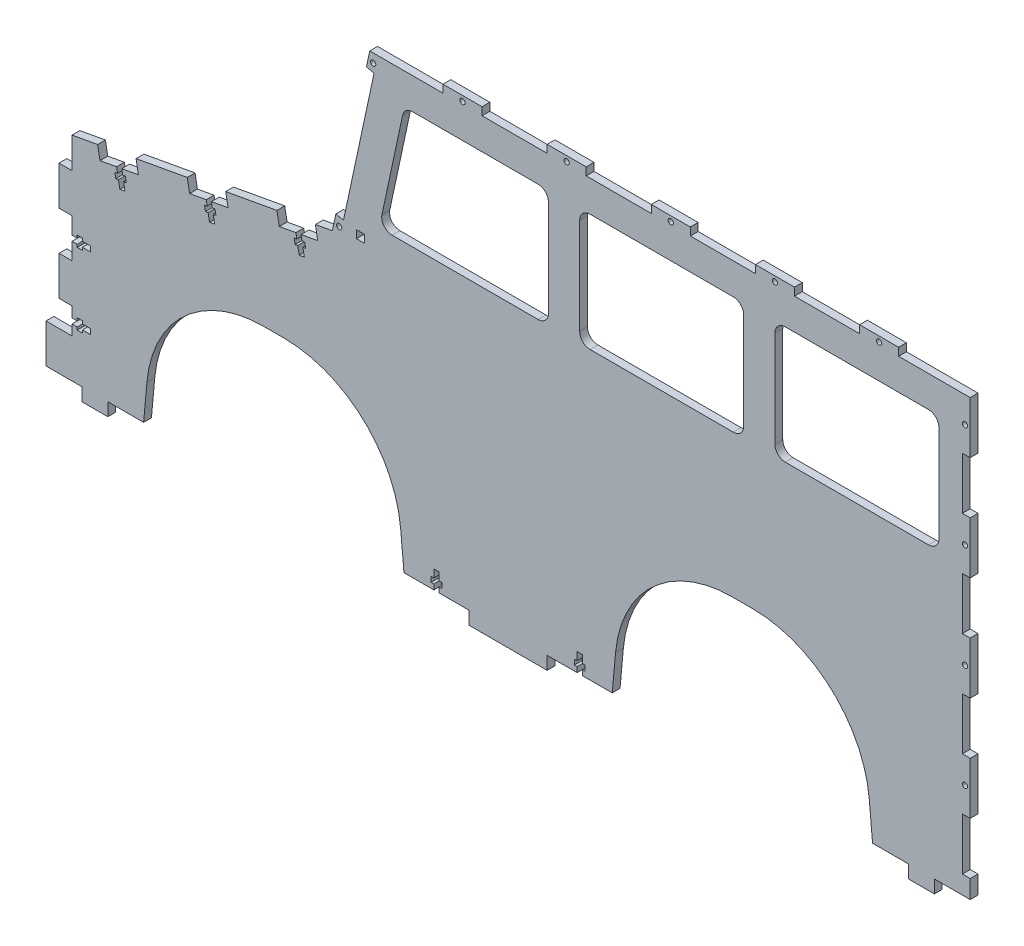
SolidWorks part; units mm, degrees
ref_plane "Front" through (0, 0, 0) normal (0, 0, 1) x (1, 0, 0)
ref_plane "Top" through (0, 0, 0) normal (0, 1, 0) x (1, 0, 0)
ref_plane "Right" through (0, 0, 0) normal (1, 0, 0) x (0, 0, -1)
sketch "草图1" plane through (0, 0, 0) normal (0, 0, 1) x (1, 0, 0)
  line L0 (0, 0) -> (0, 85)
  line L3 (125, 175) -> (355, 175)
  line L4 (355, 175) -> (355, 0)
  line L5 (355, 0) -> (317.5, 0)
  line L7 (312.5, 60) -> (222.5, 60)
  line L9 (217.5, 0) -> (137.5, 0)
  line L11 (132.5, 60) -> (42.5, 60)
  line L13 (37.5, 0) -> (0, 0)
  line L14 (37.5, 0) -> (37.5, 5)
  line L15 (37.5, 5) -> (42.5, 60)
  line L16 (137.5, 0) -> (137.5, 5)
  line L17 (137.5, 5) -> (132.5, 60)
  line L18 (217.5, 0) -> (217.5, 5)
  line L19 (217.5, 5) -> (222.5, 60)
  line L22 (312.5, 60) -> (317.5, 5)
  line L23 (317.5, 5) -> (317.5, 0)
  line L24 (125, 175) -> (110, 105)
  line L25 (110, 105) -> (0, 85)
  dimension "D1" = 85
  dimension "D2" = 37.5
  dimension "D3" = 0
  dimension "D4" = 100
  dimension "D5" = 90
  dimension "D6" = 80
  dimension "D7" = 100
  dimension "D8" = 90
  dimension "D9" = 37.5
  dimension "D10" = 70
  dimension "D11" = 20
  dimension "D12" = 5
  dimension "D13" = 15
  dimension "D15" = 60
  dimension "D16" = 60
  dimension "D18" = 230
  dimension "D19" = 5
  dimension "D20" = 5
  dimension "D21" = 5
extrude "凸台-拉伸1" add sketch "草图1" along normal blind 3
sketch "草图2" plane through (0, 0, 3) normal (0, 0, 1) x (1, 0, 0)
  line L0 (355, 175) -> (125, 175) construction
  circle A1 centre (200, 173) radius 1
  circle A2 centre (240, 173) radius 1
  circle A3 centre (280, 173) radius 1
  circle A4 centre (320, 173) radius 1
  circle A5 centre (160, 173) radius 1
  dimension "D2" = 2
  dimension "D3" = 40
  dimension "D4" = 2
  dimension "D7" = 0
  dimension "D8" = 40
  dimension "D9" = 40
  dimension "D10" = 2
  dimension "D11" = 40
  dimension "D12" = 0
sketch "草图3" plane through (0, 0, 3) normal (0, 0, 1) x (1, 0, 0)
  line L0 (355, 175) -> (125, 175) construction
  line L4 (167.5, 175) -> (167.5, 172)
  line L5 (355, 172) -> (327.5, 172)
  line L9 (207.5, 175) -> (207.5, 172)
  line L13 (247.5, 175) -> (247.5, 172)
  line L17 (287.5, 175) -> (287.5, 172)
  line L19 (312.5, 175) -> (312.5, 172)
  line L21 (327.5, 175) -> (327.5, 172)
  line L22 (355, 0) -> (355, 175) construction
  line L25 (192.5, 172) -> (167.5, 172)
  line L26 (232.5, 172) -> (207.5, 172)
  line L27 (272.5, 172) -> (247.5, 172)
  line L28 (312.5, 172) -> (287.5, 172)
  line L31 (167.5, 175) -> (192.5, 175)
  line L32 (207.5, 175) -> (232.5, 175)
  line L33 (247.5, 175) -> (272.5, 175)
  line L34 (287.5, 175) -> (312.5, 175)
  line L35 (327.5, 175) -> (355, 175)
  line L36 (355, 175) -> (355, 172)
  line L37 (152.5, 175) -> (152.5, 172)
  line L38 (192.5, 175) -> (192.5, 172)
  line L39 (232.5, 175) -> (232.5, 172)
  line L40 (272.5, 175) -> (272.5, 172)
  line L41 (152.5, 172) -> (124.3571, 172)
  line L42 (125, 175) -> (110, 105) construction
  line L44 (152.5, 175) -> (125, 175)
  line L45 (125, 175) -> (124.3571, 172)
  circle A4 centre (320, 173) radius 1 construction
  dimension "D15" = 7.5
  dimension "D1" = 15
  dimension "D2" = 3
  dimension "D4" = 3
  dimension "D5" = 15
  dimension "D7" = 3
  dimension "D8" = 15
  dimension "D10" = 3
  dimension "D11" = 15
  dimension "D13" = 15
  dimension "D14" = 3
extrude "切除-拉伸1" cut sketch "草图3" against normal through all
extrude "切除-拉伸2" cut sketch "草图2" against normal through all
sketch "草图4" plane through (0, 0, 3) normal (0, 0, 1) x (1, 0, 0)
  line L0 (355, 0) -> (355, 172) construction
  line L1 (327.5, 172) -> (355, 172) construction
  circle A0 centre (353, 162) radius 1
  circle A1 centre (353, 122) radius 1
  circle A2 centre (353, 82) radius 1
  circle A3 centre (353, 42) radius 1
  dimension "D1" = 2
  dimension "D2" = 2
  dimension "D3" = 2
  dimension "D4" = 40
  dimension "D5" = 40
  dimension "D6" = 2
  dimension "D7" = 40
  dimension "D8" = 10
extrude "切除-拉伸3" cut sketch "草图4" against normal through all
sketch "草图5" plane through (0, 0, 3) normal (0, 0, 1) x (1, 0, 0)
  line L0 (355, 0) -> (355, 172) construction
  line L1 (355, 152) -> (352, 152)
  line L2 (355, 152) -> (355, 132)
  line L3 (355, 132) -> (352, 132)
  line L4 (352, 152) -> (352, 132)
  line L6 (355, 112) -> (352, 112)
  line L7 (355, 112) -> (355, 92)
  line L8 (355, 92) -> (352, 92)
  line L9 (352, 112) -> (352, 92)
  line L10 (355, 72) -> (352, 72)
  line L11 (355, 72) -> (355, 52)
  line L12 (355, 52) -> (352, 52)
  line L13 (352, 72) -> (352, 52)
  line L14 (355, 32) -> (352, 32)
  line L15 (355, 32) -> (355, 12)
  line L16 (355, 12) -> (352, 12)
  line L17 (352, 32) -> (352, 12)
  circle A0 centre (353, 162) radius 1 construction
  circle A1 centre (353, 122) radius 1 construction
  circle A2 centre (353, 82) radius 1 construction
  circle A3 centre (353, 42) radius 1 construction
  dimension "D1" = 10
  dimension "D2" = 3
  dimension "D3" = 20
  dimension "D4" = 3
  dimension "D5" = 10
  dimension "D6" = 20
  dimension "D7" = 3
  dimension "D8" = 10
  dimension "D9" = 20
  dimension "D10" = 3
  dimension "D11" = 20
  dimension "D12" = 10
extrude "切除-拉伸4" cut sketch "草图5" against normal through all
sketch "草图6" plane through (0, 0, 3) normal (0, 0, 1) x (1, 0, 0)
  line L0 (137.5, 0) -> (217.5, 0) construction
  line L1 (162.5, 0) -> (109.536, 0)
  line L2 (162.5, 0) -> (162.5, 5)
  line L3 (162.5, 5) -> (109.536, 5)
  line L4 (109.536, 0) -> (109.536, 5)
  line L6 (192.5, 0) -> (242.7479, 0)
  line L7 (192.5, 0) -> (192.5, 5)
  line L8 (192.5, 5) -> (242.7479, 5)
  line L9 (242.7479, 0) -> (242.7479, 5)
  point P10 (177.5, 0)
  dimension "D1" = 5
  dimension "D2" = 5
  dimension "D3" = 15
  dimension "D4" = 15
extrude "切除-拉伸5" cut sketch "草图6" against normal through all
sketch "草图7" plane through (0, 0, 3) normal (0, 0, 1) x (1, 0, 0)
  line L0 (0, 0) -> (37.5, 0) construction
  line L1 (13.75, 0) -> (-10.7499, 0)
  line L2 (13.75, 0) -> (13.75, 5)
  line L3 (13.75, 5) -> (-10.7499, 5)
  line L4 (-10.7499, 0) -> (-10.7499, 5)
  line L5 (317.5, 0) -> (355, 0) construction
  line L6 (23.75, 0) -> (49.3843, 0)
  line L7 (23.75, 0) -> (23.75, 5)
  line L8 (23.75, 5) -> (49.3843, 5)
  line L9 (49.3843, 0) -> (49.3843, 5)
  line L10 (300.5943, 5) -> (331.25, 5)
  line L11 (300.5943, 5) -> (300.5943, 0)
  line L12 (300.5943, 0) -> (331.25, 0)
  line L13 (331.25, 5) -> (331.25, 0)
  line L14 (355, 0) -> (355, 12) construction
  line L15 (341.25, 5) -> (355, 5)
  line L16 (341.25, 5) -> (341.25, 0)
  line L17 (341.25, 0) -> (355, 0)
  line L18 (355, 5) -> (355, 0)
  point P10 (18.75, 0)
  point P17 (336.25, 0)
  dimension "D1" = 5
  dimension "D2" = 5
  dimension "D3" = 5
  dimension "D4" = 5
  dimension "D5" = 5
  dimension "D6" = 0
  dimension "D7" = 5
  dimension "D8" = 5
  dimension "D9" = 5
  dimension "D10" = 0
extrude "切除-拉伸6" cut sketch "草图7" against normal through all
sketch "草图11" plane through (0, 0, 3) normal (0, 0, 1) x (1, 0, 0)
  line L0 (114.2752, 110.6329) -> (111.3417, 111.2615)
  line L1 (124.3571, 172) -> (110, 105) construction
  line L2 (114.2752, 110.6329) -> (111.3417, 111.2615) construction
  line L3 (111.3417, 111.2615) -> (123.0754, 166.0184)
  line L4 (123.0754, 166.0184) -> (126.0088, 165.3898)
  line L5 (126.0088, 165.3898) -> (114.2752, 110.6329)
extrude "切除-拉伸10" cut sketch "草图11" against normal through all
sketch "草图12" plane through (0, 0, 3) normal (0, 0, 1) x (1, 0, 0)
  line L0 (0, 85) -> (0, 5) construction
  line L1 (0, 20) -> (10, 20)
  line L2 (0, 20) -> (0, 134.036)
  line L3 (0, 134.036) -> (10, 134.036)
  line L4 (10, 20) -> (10, 134.036)
  line L5 (13.75, 5) -> (0, 5) construction
  dimension "D1" = 10
  dimension "D2" = 15
extrude "切除-拉伸11" cut sketch "草图12" against normal through all
sketch "草图13" plane through (0, 0, 3) normal (0, 0, 1) x (1, 0, 0)
  line L0 (10, 20) -> (10, 86.8182) construction
  line L1 (10, 30) -> (5, 30)
  line L2 (10, 30) -> (10, 45)
  line L3 (10, 45) -> (5, 45)
  line L4 (5, 30) -> (5, 45)
  line L5 (0, 20) -> (10, 20) construction
  line L7 (10, 60) -> (5, 60)
  line L8 (10, 60) -> (10, 75)
  line L9 (10, 75) -> (5, 75)
  line L10 (5, 60) -> (5, 75)
  dimension "D1" = 5
  dimension "D2" = 15
  dimension "D3" = 10
  dimension "D4" = 15
  dimension "D5" = 15
extrude "凸台-拉伸2" add sketch "草图13" against normal blind 3
sketch "草图15" plane through (0, 0, 3) normal (0, 0, 1) x (1, 0, 0)
  line L2 (35.4912, 86.371) -> (34.5967, 91.2903)
  line L3 (110, 105) -> (10, 86.8182) construction
  line L5 (54.2741, 94.868) -> (55.1686, 89.9487)
  line L6 (55.1686, 89.9487) -> (69.9266, 92.632)
  line L7 (69.9266, 92.632) -> (69.0322, 97.5513)
  line L8 (69.0322, 97.5513) -> (54.2741, 94.868)
  line L9 (88.7096, 101.129) -> (89.604, 96.2097)
  line L10 (89.604, 96.2097) -> (104.3621, 98.8929)
  line L11 (104.3621, 98.8929) -> (103.4676, 103.8123)
  line L12 (103.4676, 103.8123) -> (88.7096, 101.129)
  line L13 (35.4912, 86.371) -> (20.7331, 83.6877)
  line L14 (20.7331, 83.6877) -> (19.8387, 88.607)
  line L15 (19.8387, 88.607) -> (34.5967, 91.2903)
  dimension "D1" = 10
  dimension "D2" = 5
  dimension "D3" = 5
  dimension "D4" = 15
  dimension "D5" = 20
  dimension "D6" = 15
  dimension "D7" = 5
  dimension "D8" = 20
  dimension "D9" = 15
extrude "切除-拉伸12" cut sketch "草图15" against normal through all
fillet "圆角1" radius 45 4 edges at (312.5, 60, 1.5) (222.5, 60, 1.5) (132.5, 60, 1.5) (42.5, 60, 1.5)
sketch "草图16" plane through (0, 0, 3) normal (0, 0, 1) x (1, 0, 0)
  line L0 (247.5, 175) -> (232.5, 175) construction
  line L1 (205, 160) -> (268, 160)
  line L2 (205, 160) -> (205, 115)
  line L3 (205, 115) -> (268, 115)
  line L4 (268, 160) -> (268, 115)
  line L5 (280, 160) -> (343, 160)
  line L6 (280, 160) -> (280, 115)
  line L7 (280, 115) -> (343, 115)
  line L8 (343, 160) -> (343, 115)
  line L9 (355, 152) -> (355, 172) construction
  line L10 (128, 115) -> (193, 115)
  line L11 (193, 115) -> (193, 160)
  line L12 (193, 160) -> (137.6429, 160)
  line L13 (137.6429, 160) -> (128, 115)
  line L14 (114.2752, 110.6329) -> (126.0088, 165.3898) construction
  line L15 (167.5, 175) -> (152.5, 175) construction
  dimension "D1" = 63
  dimension "D2" = 45
  dimension "D3" = 63
  dimension "D4" = 45
  dimension "D5" = 12
  dimension "D6" = 0
  dimension "D7" = 15
  dimension "D8" = 12
  dimension "D9" = 0
  dimension "D10" = 65
  dimension "D11" = 12
  dimension "D12" = 15
extrude "切除-拉伸13" cut sketch "草图16" against normal through all
fillet "圆角2" radius 4 12 edges at (343, 160, 1.5) (343, 115, 1.5) (280, 160, 1.5) (280, 115, 1.5) (268, 160, 1.5) (268, 115, 1.5) (205, 115, 1.5) (205, 160, 1.5) (193, 160, 1.5) (193, 115, 1.5) (128, 115, 1.5) (137.6429, 160, 1.5)
sketch "草图17" plane through (0, 0, 3) normal (0, 0, 1) x (1, 0, 0)
  line L0 (132.9479, 115) -> (189, 115) construction
  line L1 (119.2752, 110) -> (122.2752, 110)
  line L2 (119.2752, 110) -> (119.2752, 107)
  line L3 (119.2752, 107) -> (122.2752, 107)
  line L4 (122.2752, 110) -> (122.2752, 107)
  dimension "D1" = 3
  dimension "D2" = 3
  dimension "D3" = 5
  dimension "D4" = 5
extrude "切除-拉伸14" cut sketch "草图17" against normal through all
sketch "草图18" plane through (0, 0, 3) normal (0, 0, 1) x (1, 0, 0)
  line L0 (162.5, 5) -> (137.5, 5) construction
  line L1 (149, 5) -> (151, 5)
  line L2 (149, 5) -> (149, 7)
  line L3 (149, 12) -> (151, 12)
  line L4 (151, 5) -> (151, 7)
  line L5 (147.95, 9) -> (149, 9)
  line L6 (147.95, 9) -> (147.95, 7)
  line L7 (147.95, 7) -> (149, 7)
  line L8 (152.05, 9) -> (152.05, 7)
  line L9 (151, 7) -> (152.05, 7)
  line L10 (149, 9) -> (149, 12)
  line L11 (151, 9) -> (152.05, 9)
  line L12 (151, 9) -> (151, 12)
  point P8 (150, 5)
  point P11 (150, 5)
  dimension "D1" = 2
  dimension "D2" = 7
  dimension "D3" = 2
  dimension "D4" = 4.1
  dimension "D5" = 1.05
  dimension "D6" = 2
  dimension "D7" = 0
  dimension "D8" = 0
extrude "切除-拉伸15" cut sketch "草图18" against normal through all
pattern_linear "阵列(线性)1" count 2 spacing 55 along (1, 0, 0) of "切除-拉伸15"
sketch "草图19" plane through (0, 0, 3) normal (0, 0, 1) x (1, 0, 0)
  line L0 (10, 45) -> (10, 60) construction
  line L1 (10, 53.5) -> (12, 53.5)
  line L2 (10, 53.5) -> (10, 51.5)
  line L3 (10, 51.5) -> (12, 51.5)
  line L4 (17, 53.5) -> (17, 51.5)
  line L5 (12, 54.55) -> (14, 54.55)
  line L6 (12, 54.55) -> (12, 53.5)
  line L7 (12, 50.45) -> (14, 50.45)
  line L8 (14, 54.55) -> (14, 53.5)
  line L9 (14, 51.5) -> (14, 50.45)
  line L10 (14, 53.5) -> (17, 53.5)
  line L11 (12, 51.5) -> (12, 50.45)
  line L12 (14, 51.5) -> (17, 51.5)
  line L13 (10, 26) -> (12, 26)
  line L14 (10, 26) -> (10, 24)
  line L15 (10, 24) -> (12, 24)
  line L16 (17, 26) -> (17, 24)
  line L17 (12, 27.05) -> (14, 27.05)
  line L18 (12, 27.05) -> (12, 26)
  line L19 (12, 22.95) -> (14, 22.95)
  line L20 (14, 27.05) -> (14, 26)
  line L21 (14, 24) -> (14, 22.95)
  line L22 (14, 26) -> (17, 26)
  line L23 (12, 24) -> (12, 22.95)
  line L24 (14, 24) -> (17, 24)
  line L25 (10, 20) -> (10, 30) construction
  line L26 (27.1283, 84.8504) -> (29.096, 85.2082)
  line L27 (29.096, 85.2082) -> (29.4538, 83.2405)
  line L28 (30.3482, 78.3211) -> (28.3805, 77.9634)
  line L29 (28.3805, 77.9634) -> (27.8438, 80.915)
  line L30 (26.453, 82.6949) -> (27.4861, 82.8827)
  line L31 (30.4869, 83.4283) -> (30.8446, 81.4606)
  line L32 (30.8446, 81.4606) -> (29.8116, 81.2727)
  line L33 (26.8108, 80.7271) -> (26.453, 82.6949)
  line L34 (20.7331, 83.6877) -> (35.4912, 86.371) construction
  line L35 (29.4538, 83.2405) -> (30.4869, 83.4283)
  line L36 (27.4861, 82.8827) -> (27.1283, 84.8504)
  line L37 (29.8116, 81.2727) -> (30.3482, 78.3211)
  line L38 (27.8438, 80.915) -> (26.8108, 80.7271)
  point P8 (10, 52.5)
  point P11 (10, 52.5)
  point P24 (10, 25)
  point P31 (10, 25)
  point P42 (28.1122, 85.0293)
  point P43 (28.1122, 85.0293)
  dimension "D1" = 2
  dimension "D2" = 7
  dimension "D3" = 4.1
  dimension "D4" = 1.05
  dimension "D5" = 2
  dimension "D6" = 2
  dimension "D7" = 0
  dimension "D8" = 0
  dimension "D9" = 2
  dimension "D10" = 4.1
  dimension "D11" = 1.05
  dimension "D12" = 2
  dimension "D13" = 2
  dimension "D14" = 0
  dimension "D15" = 0
  dimension "D16" = 2
  dimension "D17" = 7
  dimension "D18" = 4.1
  dimension "D19" = 1.05
  dimension "D20" = 2
  dimension "D21" = 2
  dimension "D22" = 0
  dimension "D23" = 0
  dimension "D24" = 7
extrude "切除-拉伸16" cut sketch "草图19" against normal through all
sketch "草图20" plane through (0, 0, 3) normal (0, 0, 1) x (1, 0, 0)
  line L0 (61.5637, 91.1114) -> (61.9215, 89.1437)
  line L1 (55.1686, 89.9487) -> (69.9266, 92.632) construction
  line L2 (62.8159, 84.2243) -> (64.7837, 84.5821)
  line L3 (64.7837, 84.5821) -> (64.247, 87.5337)
  line L4 (63.5315, 91.4692) -> (61.5637, 91.1114)
  line L5 (60.8884, 88.9559) -> (61.9215, 89.1437)
  line L6 (64.9223, 89.6893) -> (65.2801, 87.7216)
  line L7 (65.2801, 87.7216) -> (64.247, 87.5337)
  line L8 (61.2462, 86.9881) -> (60.8884, 88.9559)
  line L9 (95.9992, 97.3724) -> (96.3569, 95.4047)
  line L10 (89.604, 96.2097) -> (104.3621, 98.8929) construction
  line L11 (97.2514, 90.4853) -> (99.2191, 90.8431)
  line L12 (99.2191, 90.8431) -> (98.6825, 93.7947)
  line L13 (97.9669, 97.7302) -> (95.9992, 97.3724)
  line L14 (95.3239, 95.2169) -> (96.3569, 95.4047)
  line L15 (99.3577, 95.9503) -> (99.7155, 93.9825)
  line L16 (99.7155, 93.9825) -> (98.6825, 93.7947)
  line L17 (95.6817, 93.2491) -> (95.3239, 95.2169)
  line L18 (98.3247, 95.7625) -> (99.3577, 95.9503)
  line L19 (96.7147, 93.4369) -> (97.2514, 90.4853)
  line L20 (98.3247, 95.7625) -> (97.9669, 97.7302)
  line L21 (96.7147, 93.4369) -> (95.6817, 93.2491)
  line L22 (63.8892, 89.5015) -> (64.9223, 89.6893)
  line L23 (62.2793, 87.176) -> (62.8159, 84.2243)
  line L24 (63.8892, 89.5015) -> (63.5315, 91.4692)
  line L25 (62.2793, 87.176) -> (61.2462, 86.9881)
  point P9 (62.5476, 91.2903)
  point P11 (62.5476, 91.2903)
  point P22 (96.983, 97.5513)
  point P23 (96.983, 97.5513)
  dimension "D1" = 2
  dimension "D2" = 7
  dimension "D3" = 2
  dimension "D4" = 4.1
  dimension "D5" = 1.05
  dimension "D6" = 2
  dimension "D7" = 0
  dimension "D8" = 2
  dimension "D9" = 7
  dimension "D10" = 4.1
  dimension "D11" = 1.05
  dimension "D12" = 2
  dimension "D13" = 2
  dimension "D14" = 0
extrude "切除-拉伸17" cut sketch "草图20" against normal through all
sketch "草图21" plane through (0, 0, 3) normal (0, 0, 1) x (1, 0, 0)
  line L0 (124.3571, 172) -> (123.0754, 166.0184) construction
  line L1 (111.3417, 111.2615) -> (110, 105) construction
  circle A0 centre (125.6719, 168.5901) radius 1
  circle A1 centre (112.6265, 107.7117) radius 1
  dimension "D1" = 2
  dimension "D2" = 2
extrude "切除-拉伸18" cut sketch "草图21" against normal through all
equation "\"4、1\"=7.73063"
equation "\"4。1\"=6.29502"
